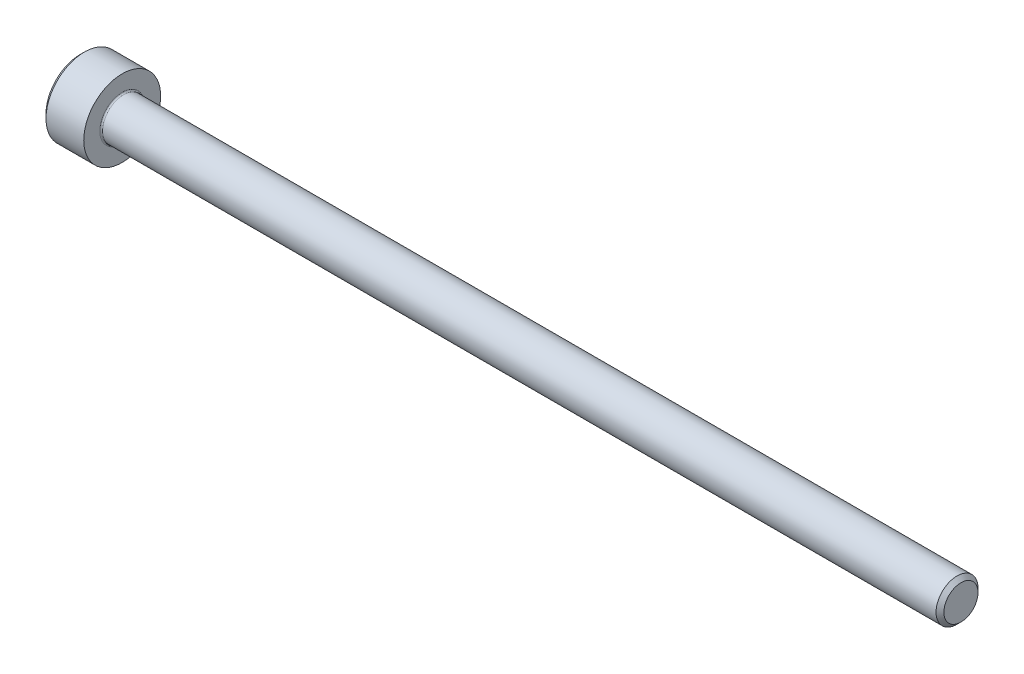
SolidWorks part; units mm, degrees
revolve "Base-Revolve" add sketch "BodySke"
sketch "BodySke" plane through (0, 0, 0) normal (0, 0, 1) x (1, 0, 0)
  line L0 (0, 0) -> (0, 2.45)
  line L1 (0.3, 2.75) -> (3, 2.75)
  line L2 (3, 2.75) -> (3, 1.5)
  line L3 (3, 1.5) -> (62.7195, 1.5)
  line L4 (63, 1.2195) -> (63, 0)
  line L5 (63, 0) -> (0, 0)
  line L6 (-31.75, 0) -> (127, 0) construction
  line L7 (0, 2.45) -> (0.3, 2.75)
  line L8 (63, 1.2195) -> (62.7195, 1.5)
  line L9 (0, -2.45) -> (0.3, -2.75) construction
  line L10 (63, -1.2195) -> (62.7195, -1.5) construction
  line L11 (3.5, 9.525) -> (3.5, 3.175) construction
  line L12 (45, 9.525) -> (45, 3.175) construction
  line L13 (13, 9.525) -> (13, 3.175) construction
  dimension "Diameter" = 3
  dimension "Head_ht" = 3
  dimension "Length" = 60
  dimension "Body_ch_ang" = 45
  dimension "Head_dia" = 5.5
  dimension "Head_ch_ang" = 45
  dimension "Minor_dia" = 2.439
  dimension "Advance" = 0.5
  dimension "Thread_nom" = 18
  dimension "Thread_length" = 50
  dimension "Head_ch_ht" = 0.3
cosmetic thread "ThreadCosmetic" [suppressed]
fillet "Fillet1" radius 0.1 1 edges at (3, 0, 1.5)
ref_plane "Plane1" through (0, 0, 0) normal (0, 0, 1) x (1, 0, 0)
ref_plane "Plane2" through (0, 0, 0) normal (0, 1, 0) x (1, 0, 0)
ref_plane "Plane3" through (0, 0, 0) normal (1, 0, 0) x (0, 0, -1)
sketch "Sketch2" plane through (0, 0, 0) normal (0, 0, 1) x (1, 0, 0)
  line L0 (0, 1.28) -> (1.3, 1.28)
  line L1 (1.3, 1.28) -> (2.039, 0)
  line L2 (-31.75, 0) -> (127, 0) construction
  line L3 (2.039, 0) -> (0, 0)
  line L4 (0, 0) -> (0, 1.28)
  line L5 (0, 2.45) -> (0, -2.45) construction
  line L6 (0, 0) -> (47.625, 0) construction
  line L7 (3, -2.75) -> (3, 2.75) construction
  dimension "D1" = 1.28
  dimension "D2" = 60
revolve "Hex-PreBroach" cut sketch "Sketch2" angle 360 about L6
sketch "Sketch3" plane through (0, 0, 0) normal (-1, 0, 0) x (0, 0.5, 0.866)
  line L0 (0.739, 1.28) -> (-0.739, 1.28)
  line L1 (-0.739, 1.28) -> (-1.478, 0)
  line L2 (0.739, 1.28) -> (1.478, 0)
  line L3 (0.739, -1.28) -> (1.478, 0)
  line L4 (0.739, -1.28) -> (-0.739, -1.28)
  line L5 (-0.739, -1.28) -> (-1.478, 0)
  dimension "D1" = 1.28
  dimension "D2" = 1.28
  dimension "Hex_size" = 2.56
extrude "Hex" cut sketch "Sketch3" against normal blind 1.3
sketch "Sketch4" plane through (0, 0, 0) normal (-1, 0, 0) x (0, 0, 1)
  line L0 (0, 0) -> (1.4605, 0)
  line L1 (0, 0) -> (6.1484, 3.5498) construction
  line L2 (0, 0) -> (0.7302, 1.2648)
  line L3 (1.2009, 0.3267) -> (1.3933, 0.4378)
  line L4 (0.8834, 0.8767) -> (1.0758, 0.9877)
  arc A0 (1.2009, 0.3267) -> (0.8834, 0.8767) centre (0, 0) ccw
  arc A1 (1.4605, 0) -> (1.3933, 0.4378) centre (0, 0) ccw
  arc A2 (0.7302, 1.2648) -> (1.0758, 0.9877) centre (0, 0) cw
  dimension "D1" = 30
  dimension "D2" = 60
  dimension "Spline_p_dim" = 0.635
  dimension "D3" = 0.3175
extrude "Spline" [suppressed] cut sketch "Sketch4" against normal blind 1.3
pattern_circular "CirPattern1" [suppressed] count 6 every 60
sketch "Sketch5" plane through (0, 0, 0) normal (0, 0, 1) x (1, 0, 0)
  line L0 (-31.75, 0) -> (127, 0) construction
  line L2 (0, 2.45) -> (0, -2.45) construction
  circle A0 centre (1.2, 0) radius 0.475
  dimension "Drilled_hole_dia" = 0.95
  dimension "Drilled_hole_loc" = 1.2
extrude "Hole" [suppressed] cut sketch "Sketch5" against normal through all and the other way through all
pattern_circular "Drilled-4" [suppressed] count 2 every 60
pattern_circular "Drilled-6" [suppressed] count 3 every 60
sketch "ThdSchSke" plane through (0, 0, 0) normal (0, 0, 1) x (1, 0, 0)
  line L0 (45, -1.2195) -> (44.8036, -1.5)
  line L1 (45, -1.2195) -> (45.1964, -1.5)
  line L2 (45.1964, -1.5) -> (45.1964, -1.875)
  line L3 (-3.175, 0) -> (5.1513, 0) construction
  line L5 (45.1964, -1.875) -> (44.8036, -1.875)
  line L6 (44.8036, -1.875) -> (44.8036, -1.5)
  line L7 (0, 2.45) -> (0, -2.45) construction
  dimension "Thread_minor" = 2.439
  dimension "Diameter" = 3
revolve "ThreadSchematic" [suppressed] cut sketch "ThdSchSke" angle 360 about L3
pattern_linear "ThdSchPat" [suppressed]
equation "\"D2@Sketch3\" = \"Hex_size@Sketch3\" / 2"
equation "\"D1@Sketch3\" = \"Hex_size@Sketch3\" / 2"
equation "\"D1@Sketch2\" = \"Hex_size@Sketch3\" / 2"
equation "\"D3@Sketch4\" = \"Spline_p_dim@Sketch4\" / 2"
equation "\"Thread_minor@ThreadCosmetic\"  =  \"Minor_dia@BodySke\""
equation "\"D2@CirPattern1\" = 360 / \"Num_teeth@CirPattern1\""
equation "\"Wall_thickness@Sketch2\" = \"Head_ht@BodySke\" - \"Key_eng@Hex\""
equation "\"Thread_length@ThreadCosmetic\" = ((sgn( (\"Length@BodySke\" - \"Advance@BodySke\" ) - \"Thread_nom@BodySke\" )-1)*( (\"Length@BodySke\" - \"Advance@BodySke\" ) - \"Thread_nom@BodySke\" ))/-2+ \"Thread_nom@BodySke\""
equation "\"Thread_minor@ThdSchSke\" = \"Minor_dia@BodySke\""
equation "\"Diameter@ThdSchSke\" = \"Diameter@BodySke\""
equation "\"Overcut@ThdSchSke\" = \"Diameter@BodySke\" * 1.25"
equation "\"Start@ThdSchSke\" = \"Head_ht@BodySke\" + \"Length@BodySke\" - \"Thread_length@ThreadCosmetic\"  '---Non-countersunk---"
equation "\"Num_threads@ThdSchPat\" = int( \"Thread_length@ThreadCosmetic\" / \"Advance@BodySke\" + 0.999 )  + 1"
equation "\"Advance@ThdSchPat\" = \"Thread_length@ThreadCosmetic\" /  (\"Num_threads@ThdSchPat\" - 1) 'relax it"
equation "\"Num_threads@ThdSchPat\" = \"Num_threads@ThdSchPat\" - sgn( \"Num_threads@ThdSchPat\" - 1) '---chamfered tips only---"
